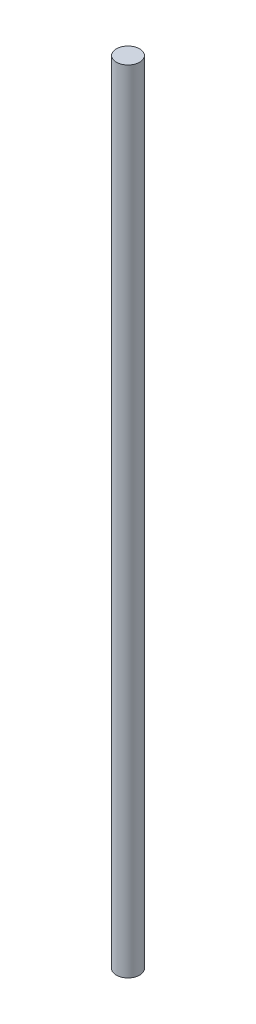
SolidWorks part; units mm, degrees
ref_plane "Front Plane" through (0, 0, 0) normal (0, 0, 1) x (1, 0, 0)
ref_plane "Top Plane" through (0, 0, 0) normal (0, 1, 0) x (1, 0, 0)
ref_plane "Right Plane" through (0, 0, 0) normal (1, 0, 0) x (0, 0, -1)
sketch "Sketch1" plane through (0, 0, 0) normal (0, 1, 0) x (1, 0, 0)
  circle A0 centre (0, 0) radius 0.5
  dimension "D1" = 1
extrude "Boss-Extrude1" add sketch "Sketch1" along normal blind 34
